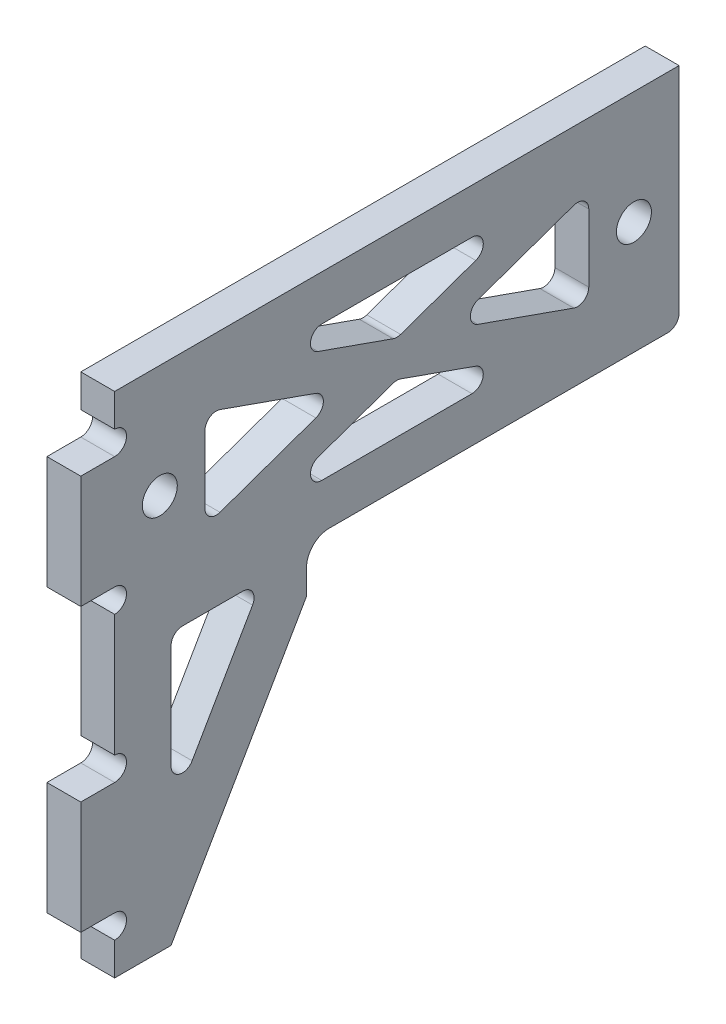
SolidWorks part; units mm, degrees
material "环氧树脂板"
ref_plane "前视基准面" through (0, 0, 0) normal (0, 0, 1) x (1, 0, 0)
ref_plane "上视基准面" through (0, 0, 0) normal (0, 1, 0) x (1, 0, 0)
ref_plane "右视基准面" through (0, 0, 0) normal (1, 0, 0) x (0, 0, -1)
sketch "草图1" plane through (0, 0, 0) normal (1, 0, 0) x (0, 0, -1)
  line L0 (0, 0) -> (-8.6288, 0) construction
  line L1 (25, -10) -> (-25, -10) construction
  line L2 (25, -10) -> (25, 10)
  line L3 (25, 10) -> (-25, 10)
  line L4 (-25, -10) -> (-25, -5)
  line L5 (25, -10) -> (-25, 10) construction
  line L6 (25, 10) -> (-25, -10) construction
  line L7 (-25, 5) -> (-28, 5)
  line L8 (-28, 5) -> (-28, -5)
  line L9 (-28, -5) -> (-25, -5)
  line L10 (-25, 5) -> (-25, 10)
  line L11 (-17, -4.4093) -> (-4.5069, 0)
  line L12 (17, -6) -> (-17, -6) construction
  line L13 (17, -6) -> (17, 6) construction
  line L14 (17, 6) -> (-17, 6) construction
  line L15 (-17, -6) -> (-17, 6) construction
  line L16 (17, -6) -> (-17, 6) construction
  line L17 (17, 6) -> (-17, -6) construction
  line L18 (-12.4931, -6) -> (0, -1.5907)
  line L19 (-12.4931, 6) -> (0, 1.5907)
  line L20 (-17, 4.4093) -> (-4.5069, 0)
  line L21 (-17, 4.4093) -> (-17, -4.4093)
  line L22 (-12.4931, -6) -> (12.4931, -6)
  line L23 (17, -4.4093) -> (17, 4.4093)
  line L24 (12.4931, 6) -> (-12.4931, 6)
  line L25 (0, 1.5907) -> (12.4931, 6)
  line L26 (4.5069, 0) -> (17, -4.4093)
  line L27 (4.5069, 0) -> (17, 4.4093)
  line L28 (0, -1.5907) -> (12.4931, -6)
  line L29 (-28, 0) -> (-23.7908, 0) construction
  line L30 (-25, -20) -> (-28, -20)
  line L31 (-28, -20) -> (-28, -30)
  line L32 (-28, -30) -> (-25, -30)
  line L33 (-25, -30) -> (-25, -35)
  line L34 (-25, -35) -> (-20, -35)
  line L35 (-20, -35) -> (-8, -14.2154)
  line L36 (-8, -14.2154) -> (-8, -10)
  line L37 (-25, -20) -> (-25, -10)
  line L38 (-28, -25) -> (-23.7908, -25) construction
  line L39 (-8, -10) -> (25, -10)
  line L40 (-28, 25) -> (-23.7908, 25) construction
  line L41 (-25, 20) -> (-25, 10) construction
  line L42 (-8, 14.2154) -> (-8, 10) construction
  line L43 (-20, 35) -> (-8, 14.2154) construction
  line L44 (-25, 35) -> (-20, 35) construction
  line L45 (-25, 30) -> (-25, 35) construction
  line L46 (-28, 30) -> (-25, 30) construction
  line L47 (-28, 20) -> (-28, 30) construction
  line L48 (-25, 20) -> (-28, 20) construction
  line L50 (-20, -25) -> (-20, -11)
  line L51 (-20, -11) -> (-11.9171, -11)
  line L52 (-11.9171, -11) -> (-20, -25)
  line L53 (-20, 11) -> (-11.9171, 11) construction
  line L54 (-20, 25) -> (-20, 11) construction
  line L55 (-11.9171, 11) -> (-20, 25) construction
  circle A0 centre (-21, 0) radius 1.55
  circle A1 centre (21, 0) radius 1.55
  circle A2 centre (-25, 6.05) radius 1.05
  circle A3 centre (-25, -6.05) radius 1.05
  circle A4 centre (-25, -31.05) radius 1.05
  circle A5 centre (-25, -18.95) radius 1.05
  circle A6 centre (-25, 18.95) radius 1.05 construction
  circle A7 centre (-25, 31.05) radius 1.05 construction
  point P0 (0, 0)
  dimension "D7" = 3.1
  dimension "D8" = 2.1
  dimension "D1" = 20
  dimension "D2" = 3
  dimension "D3" = 10
  dimension "D4" = 50
  dimension "D5" = 4
  dimension "D6" = 4
  dimension "D9" = 4
  dimension "D10" = 4
  dimension "D11" = 3
  dimension "D12" = 25
  dimension "D13" = 5
  dimension "D14" = 5
  dimension "D15" = 17
  dimension "D16" = 30
  dimension "D17" = 5
  dimension "D18" = 5
  dimension "D19" = 5
extrude "凸台-拉伸1" add sketch "草图1" along normal blind 3 contours A3 L4 L1 L2 L3 L10 A2 L7 L8 L9 A1 A0 L25 L19 L24 L21 L20 L11 L26 L27 L23 L18 L28 L22
fillet "圆角1" radius 1 16 edges at (1.5, -10, -25) (1.5, -11, 20) (1.5, -25, 20) (1.5, -11, 11.9171) (1.5, -6, 12.4931) (1.5, -6, -12.4931) (1.5, -1.5907, 0) (1.5, -4.4093, -17) (1.5, 4.4093, -17) (1.5, 0, -4.5069) (1.5, 0, 4.5069) (1.5, 4.4093, 17) (1.5, 6, -12.4931) (1.5, 6, 12.4931) (1.5, 1.5907, 0) (1.5, -4.4093, 17)
fillet "圆角2" radius 2 1 edges at (1.5, -10, 8)
